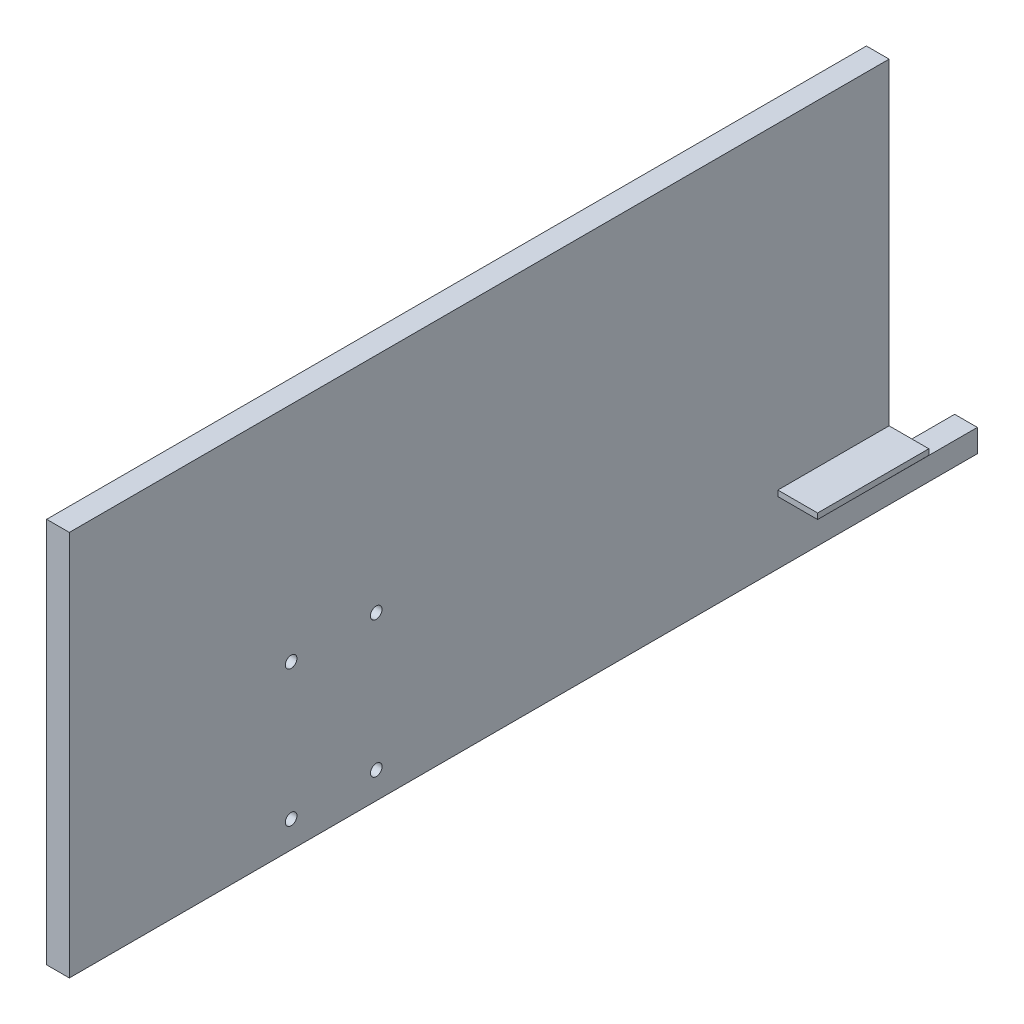
SolidWorks part; units mm, degrees
ref_plane "前视基准面" through (0, 0, 0) normal (0, 0, 1) x (1, 0, 0)
ref_plane "上视基准面" through (0, 0, 0) normal (0, 1, 0) x (1, 0, 0)
ref_plane "右视基准面" through (0, 0, 0) normal (1, 0, 0) x (0, 0, -1)
other "Configuration Table"
sketch "草图1" plane through (0, 0, 0) normal (0, 0, 1) x (1, 0, 0)
  line L9 (-10, -170) -> (10, -170)
  line L10 (-10, -170) -> (-10, 170)
  line L11 (-10, 170) -> (10, 170)
  line L12 (10, -170) -> (10, 170)
  line L13 (-10, -170) -> (10, 170) construction
  line L14 (-10, 170) -> (10, -170) construction
  point P0 (0, 0)
  dimension "D1" = 340
  dimension "D2" = 20
extrude "凸台-拉伸1" add sketch "草图1" along normal blind 800
hole_wizard "M12 螺纹孔1" positions "草图2" profile "草图3" tap size "M12" standard "GB"
sketch "草图2" plane through (10, 0, 0) normal (1, 0, 0) x (0, 0, -1)
  point P0 (-529.5994, -26.4214)
  point P2 (-529.5994, -146.4214)
  point P4 (-604.5994, -146.4214)
  point P6 (-604.5994, -26.4214)
sketch "草图3" plane through (10, -26.4214, 529.5994) normal (0, 1, 0) x (0, 0, -1)
  line L0 (0, 0) -> (0, 15)
  line L1 (0, 15) -> (5.1, 11.9356)
  line L2 (5.1, 11.9356) -> (5.1, 0)
  line L5 (5.1, 0) -> (0, 0)
  line L10 (0, 15) -> (-5.1, 11.9356) construction
  line L11 (0, -6.35) -> (0, 107.95) construction
  dimension "螺纹孔钻头直径" = 10.2
  dimension "螺纹孔钻头深度" = 15
  dimension "导头角度" = 118
cosmetic thread "孔螺纹线1" parameters "D1"=24, "D2"=12
cosmetic thread "孔螺纹线2" parameters "D1"=24, "D2"=12
cosmetic thread "孔螺纹线3" parameters "D1"=24, "D2"=12
cosmetic thread "孔螺纹线4" parameters "D1"=24, "D2"=12
sketch "草图5" plane through (10, 0, 0) normal (1, 0, 0) x (0, 0, -1)
  line L0 (-800, 170) -> (0, 170) construction
  line L1 (-77.75, -149.875) -> (0, -149.875)
  line L2 (-77.75, -149.875) -> (-77.75, 170)
  line L3 (-77.75, 170) -> (0, 170)
  line L4 (0, -149.875) -> (0, 170)
  line L5 (0, -170) -> (0, 170) construction
extrude "切除-拉伸1" cut sketch "草图5" against normal through all
sketch "草图6" plane through (10, 0, 0) normal (1, 0, 0) x (0, 0, -1)
  line L0 (-77.75, 170) -> (-77.75, -149.875) construction
  line L1 (-77.75, -114.8) -> (-175.75, -114.8)
  line L2 (-77.75, -114.8) -> (-77.75, -109.8)
  line L3 (-77.75, -109.8) -> (-175.75, -109.8)
  line L4 (-175.75, -114.8) -> (-175.75, -109.8)
  line L5 (-800, -170) -> (0, -170) construction
  dimension "D1" = 98
  dimension "D2" = 55.2
  dimension "D3" = 5
extrude "凸台-拉伸2" add sketch "草图6" along normal blind 35
